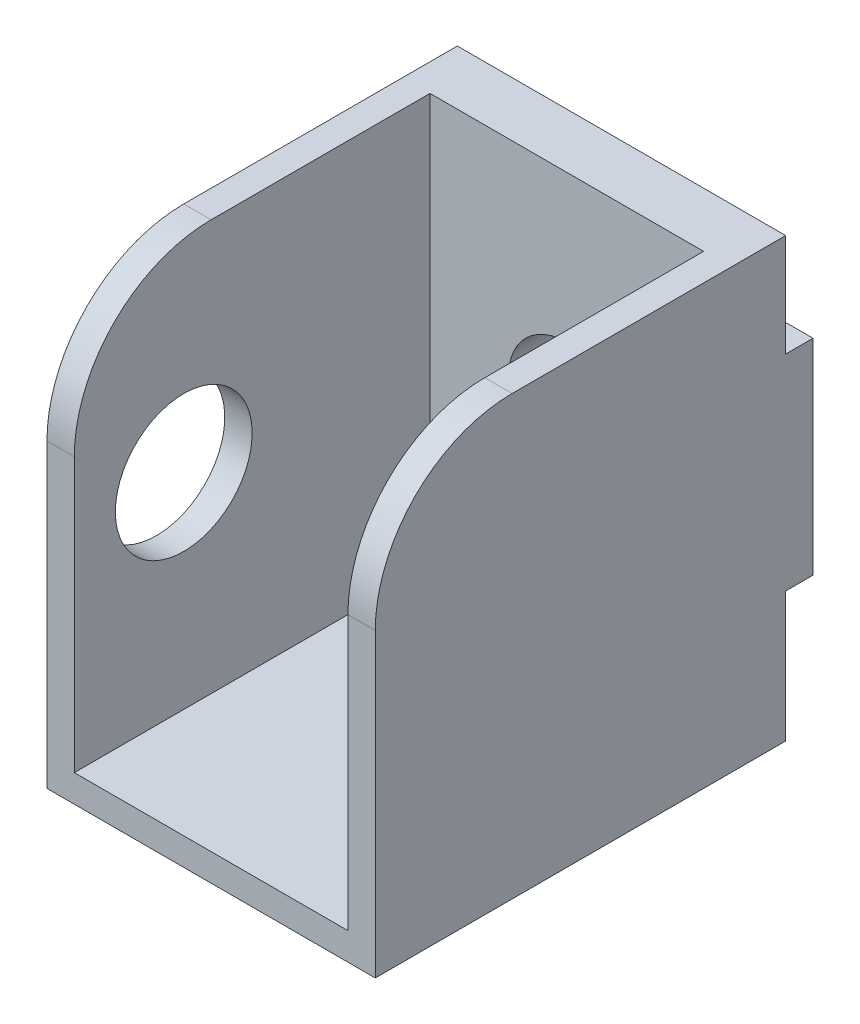
SolidWorks part; units mm, degrees
ref_plane "Front Plane" through (0, 0, 0) normal (0, 0, 1) x (1, 0, 0)
ref_plane "Top Plane" through (0, 0, 0) normal (0, 1, 0) x (1, 0, 0)
ref_plane "Right Plane" through (0, 0, 0) normal (1, 0, 0) x (0, 0, -1)
sketch "Sketch1" plane through (0, 0, 0) normal (0, 0, 1) x (1, 0, 0)
  line L1 (-10, -15) -> (10, -15)
  line L2 (-10, -15) -> (-10, 15)
  line L3 (-10, 15) -> (10, 15)
  line L4 (10, -15) -> (10, 15)
  line L5 (-10, -15) -> (10, 15) construction
  line L6 (-10, 15) -> (10, -15) construction
  circle A0 centre (0, 0) radius 4.25
  point P0 (0, 0)
  dimension "D3" = 8.5
  dimension "D1" = 20
  dimension "D2" = 30
extrude "Boss-Extrude1" add sketch "Sketch1" along normal blind 4
ref_plane "Plane1" through (0, -15, 0) normal (0, -1, 0) x (-1, 0, 0)
sketch "Sketch2" plane through (0, -15, 0) normal (0, -1, 0) x (-1, 0, 0)
  line L1 (-10, 0) -> (10, 0)
  line L2 (-10, 0) -> (-10, -30)
  line L3 (-10, -30) -> (10, -30)
  line L4 (10, 0) -> (10, -30)
  dimension "D1" = 20
  dimension "D2" = 30
extrude "Boss-Extrude2" add sketch "Sketch2" along normal blind 2
ref_plane "Plane2" through (-10, 0, 0) normal (-1, 0, 0) x (0, 0, 1)
sketch "Sketch4" plane through (-10, 0, 0) normal (-1, 0, 0) x (0, 0, 1)
  line L1 (0, 15) -> (20, 15)
  line L2 (0, 15) -> (0, -17)
  line L3 (0, -17) -> (30, -17)
  line L4 (30, 5) -> (30, -17)
  arc A0 (30, 5) -> (20, 15) centre (20, 5) ccw
  circle A1 centre (22, 0) radius 5
  dimension "D1" = 10
  dimension "D2" = 10
  dimension "D3" = 8
  dimension "D4" = 15
extrude "Boss-Extrude3" add sketch "Sketch4" along normal blind 2
ref_plane "Plane3" through (10, 0, 0) normal (1, 0, 0) x (0, 0, -1)
sketch "Sketch5" plane through (10, 0, 0) normal (1, 0, 0) x (0, 0, -1)
  line L1 (0, 15) -> (-20, 15)
  line L2 (0, 15) -> (0, -17)
  line L3 (0, -17) -> (-30, -17)
  line L4 (-30, 5) -> (-30, -17)
  arc A1 (-30, 5) -> (-20, 15) centre (-20, 5) cw
  dimension "D4" = 10
extrude "Boss-Extrude4" add sketch "Sketch5" along normal blind 2
sketch "Sketch6" plane through (0, 0, 0) normal (0, 0, -1) x (-1, 0, 0)
  line L0 (-10, 55) -> (-10, -55) construction
  line L1 (-10, -7.5) -> (-12, -7.5)
  line L2 (-10, -7.5) -> (-10, 7.5)
  line L3 (-10, 7.5) -> (-12, 7.5)
  line L4 (-12, -7.5) -> (-12, 7.5)
  line L5 (-12, -17) -> (-12, 15) construction
  line L6 (0, 16.5) -> (0, -16.5) construction
  line L7 (10, 7.5) -> (12, 7.5)
  line L8 (12, -7.5) -> (12, 7.5)
  line L9 (10, -7.5) -> (12, -7.5)
  line L10 (10, -7.5) -> (10, 7.5)
  dimension "D1" = 15
  dimension "D2" = 7.5
extrude "Boss-Extrude5" add sketch "Sketch6" along normal blind 2
